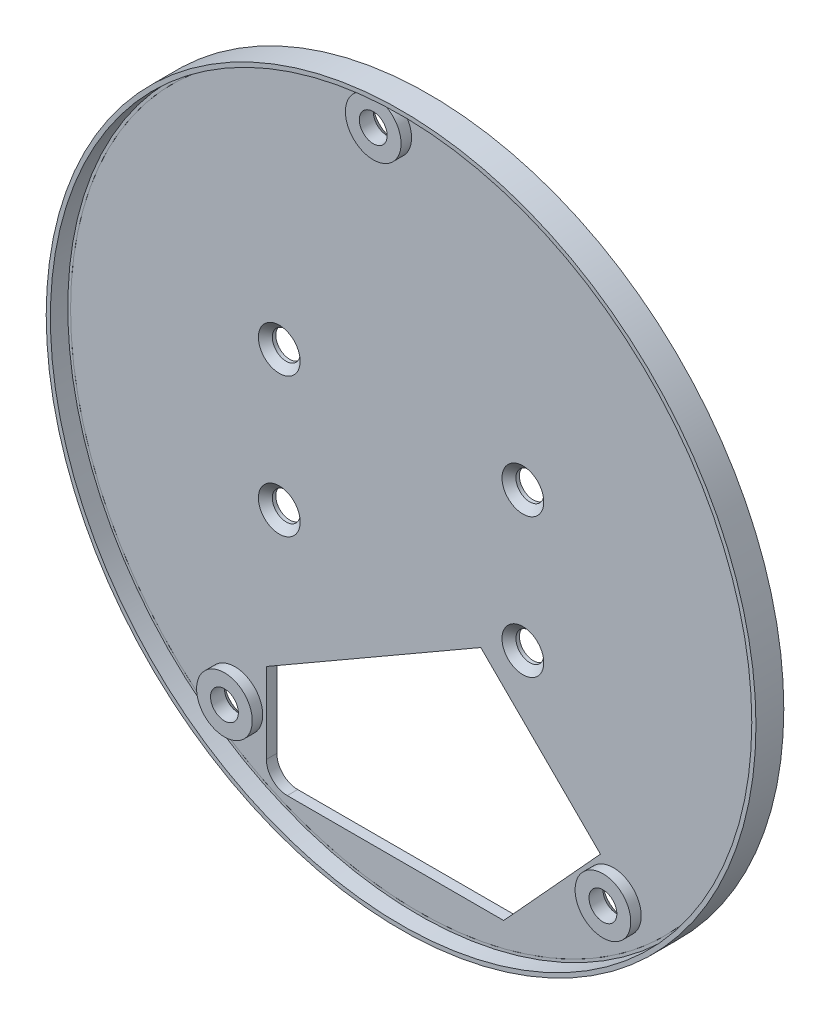
SolidWorks part; units mm, degrees
ref_plane "Front Plane" through (0, 0, 0) normal (0, 0, 1) x (1, 0, 0)
ref_plane "Top Plane" through (0, 0, 0) normal (0, 1, 0) x (1, 0, 0)
ref_plane "Right Plane" through (0, 0, 0) normal (1, 0, 0) x (0, 0, -1)
sketch "Sketch1" plane through (0, 0, 0) normal (0, 0, -1) x (-1, 0, 0)
  circle A0 centre (15.9243, 71.6108) radius 2
  circle A1 centre (15.9243, 71.6108) radius 4
  circle A2 centre (-38.4558, 73.7908) radius 2
  circle A3 centre (-38.4558, 73.7908) radius 4
  circle A10 centre (-5.4558, 154.111) radius 2
  circle A11 centre (-5.4558, 154.111) radius 4
  circle A12 centre (-5.4558, 154.111) radius 2 construction
  dimension "D1" = 8
  dimension "D2" = 4
extrude "Boss-Extrude1" add sketch "Sketch1" along normal blind 1.5
sketch "Sketch2" plane through (0, 0, -1.5) normal (0, 0, -1) x (-1, 0, 0)
  circle A0 centre (-10.4558, 108.2909) radius 49.9874
extrude "Boss-Extrude2" add sketch "Sketch2" along normal blind 1.5
sketch "Sketch3" plane through (0, 0, -1.5) normal (0, 0, 1) x (1, 0, 0)
  circle A0 centre (5.4558, 154.111) radius 2
  circle A1 centre (-15.9243, 71.6108) radius 2
  circle A2 centre (38.4558, 73.7908) radius 2
extrude "Cut-Extrude1" cut sketch "Sketch3" against normal up to next
chamfer "Chamfer1" distance 1 angle 45 3 edges at (36.4558, 73.7908, -3) (-17.9243, 71.6108, -3) (3.4558, 154.111, -3)
sketch "Sketch4" plane through (0, 0, -3) normal (0, 0, -1) x (-1, 0, 0)
  line L0 (-37.2524, 77.8928) -> (-19.4089, 95.6539) construction
  line L1 (1.6092, 63.3328) -> (-22.6924, 63.3328) construction
  line L3 (-36.5989, 78.5432) -> (-19.4089, 95.6539)
  line L4 (1.6092, 63.3328) -> (-22.6924, 63.3328)
  line L6 (1.6092, 63.3328) -> (8.3962, 63.3328)
  line L7 (11.3962, 66.3328) -> (11.3962, 77.8928)
  line L8 (11.3962, 77.8928) -> (-19.4089, 95.6539)
  line L9 (-22.6924, 63.3328) -> (-36.5989, 78.5432)
  line L10 (-41.295, 83.2393) -> (-34.7896, 76.7339) construction
  circle A0 centre (-10.4558, 108.2909) radius 49.9874 construction
  arc A1 (11.3962, 66.3328) -> (8.3962, 63.3328) centre (8.3962, 66.3328) cw
  point P13 (11.3962, 63.3328)
  dimension "D1" = 3
extrude "Cut-Extrude7" cut sketch "Sketch4" against normal up to next
ref_plane "Plane1" through (5.823, 110.3929, 4.5899) normal (0, 0, 1) x (1, 0, 0)
sketch "Sketch5" plane through (5.823, 110.3929, -3) normal (0, 0, 1) x (1, 0, 0)
  circle A0 centre (4.6328, -2.102) radius 49.9874
  circle A1 centre (4.6328, -2.102) radius 50.9874
  dimension "D1" = 1
extrude "Boss-Extrude3" add sketch "Sketch5" along normal blind 4 separate body
sketch "Sketch6" plane through (0, 0, 1) normal (0, 0, 1) x (1, 0, 0)
  circle A0 centre (10.4558, 108.2909) radius 50.3874
  arc A1 (-39.5316, 108.2909) -> (60.4432, 108.2909) centre (10.4558, 108.2909) ccw construction
  circle A2 centre (10.4558, 108.2909) radius 49.9096
  dimension "D1" = 0.4
extrude "Cut-Extrude8" cut sketch "Sketch6" against normal blind 2.5
sketch "Sketch7" plane through (0, 0, -3) normal (0, 0, -1) x (-1, 0, 0)
  line L0 (-62.8864, 105.8505) -> (41.3665, 105.8505) construction
  line L1 (-63.8875, 105.8505) -> (-61.8853, 105.8505) construction
  circle A0 centre (-25.4558, 98.2909) radius 2
  circle A1 centre (9.5442, 98.2909) radius 2
  circle A2 centre (-25.4558, 118.2909) radius 2
  circle A3 centre (9.5442, 118.2909) radius 2
  circle A5 centre (-10.4558, 108.2909) radius 49.9874 construction
  circle A6 centre (-10.4558, 108.2909) radius 49.9874 construction
  dimension "D1" = 4
  dimension "D2" = 4
  dimension "D3" = 4
  dimension "D4" = 4
  dimension "D5" = 15
  dimension "D6" = 35
  dimension "D7" = 10
  dimension "D8" = 20
extrude "Cut-Extrude9" cut sketch "Sketch7" against normal up to next (1.5 mm away)
chamfer "Chamfer2" distance 1 angle 45 4 edges at (-11.5442, 118.2909, -1.5) (-11.5442, 98.2909, -1.5) (23.4558, 98.2909, -1.5) (23.4558, 118.2909, -1.5)
